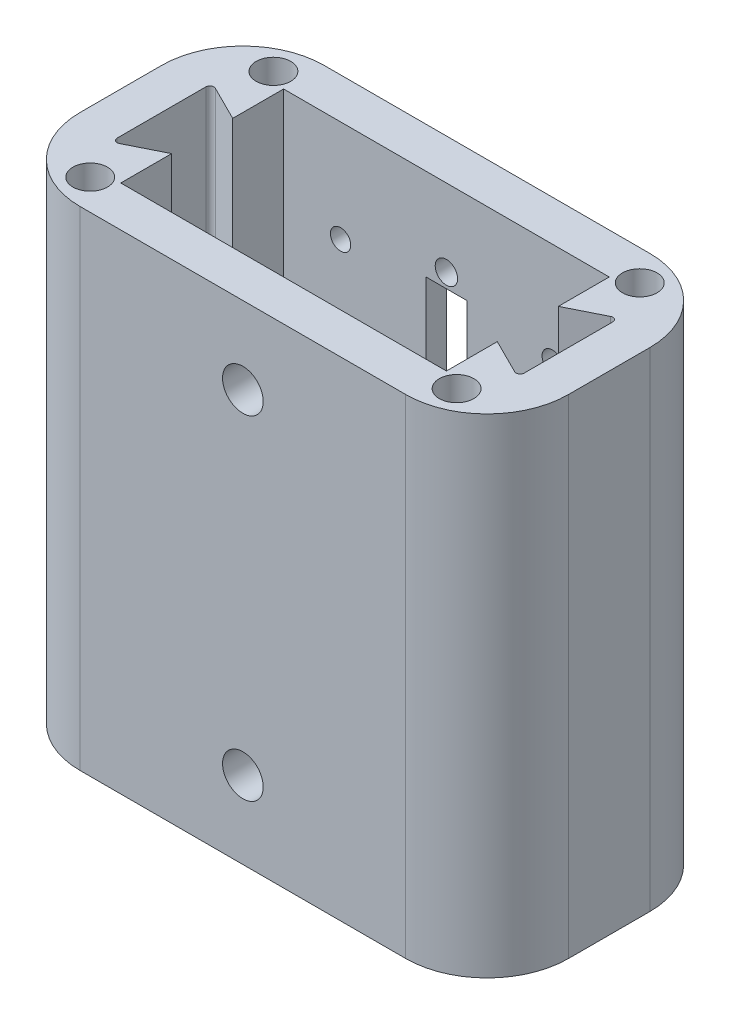
SolidWorks part; units mm, degrees
ref_plane "Front Plane" through (0, 0, 0) normal (0, 0, 1) x (1, 0, 0)
ref_plane "Top Plane" through (0, 0, 0) normal (0, 1, 0) x (1, 0, 0)
ref_plane "Right Plane" through (0, 0, 0) normal (1, 0, 0) x (0, 0, -1)
sketch "Sketch1" plane through (0, 0, 0) normal (0, 1, 0) x (1, 0, 0)
  line L1 (-30, -15) -> (30, -15)
  line L2 (-30, -15) -> (-30, 15)
  line L3 (-30, 15) -> (30, 15)
  line L4 (30, -15) -> (30, 15)
  line L5 (-30, -15) -> (30, 15) construction
  line L6 (-30, 15) -> (30, -15) construction
  line L7 (-20, -10) -> (20, -10)
  line L8 (-20, -10) -> (-20, 10)
  line L9 (-20, 10) -> (20, 10)
  line L10 (20, -10) -> (20, 10)
  line L11 (-20, -10) -> (20, 10) construction
  line L12 (-20, 10) -> (20, -10) construction
  point P0 (0, 0)
  point P7 (0, 0)
  dimension "D1" = 60
  dimension "D2" = 30
  dimension "D3" = 20
  dimension "D4" = 40
extrude "Boss-Extrude1" add sketch "Sketch1" along normal blind 5
sketch "Sketch2" plane through (0, 5, 0) normal (0, 1, 0) x (1, 0, 0)
  line L0 (20, 3.75) -> (24.2764, 5.8882)
  line L1 (25, 5.441) -> (25, -5.441)
  line L2 (24.2764, -5.8882) -> (20, -3.75)
  line L3 (20, 3.75) -> (20, -3.75) construction
  line L4 (20, -10) -> (20, 10) construction
  line L5 (0, -55) -> (0, 55) construction
  line L6 (-20, 3.75) -> (-20, -3.75) construction
  line L7 (-24.2764, -5.8882) -> (-20, -3.75)
  line L8 (-25, 5.441) -> (-25, -5.441)
  line L9 (-20, 3.75) -> (-24.2764, 5.8882)
  line L14 (30, -15) -> (30, 15)
  line L15 (30, 15) -> (-30, 15)
  line L16 (-30, 15) -> (-30, -15)
  line L17 (-30, -15) -> (30, -15)
  line L18 (30, -15) -> (30, 15)
  line L19 (30, 15) -> (-30, 15)
  line L20 (-30, 15) -> (-30, -15)
  line L21 (-30, -15) -> (30, -15)
  arc A1 (25, -5.441) -> (24.2764, -5.8882) centre (24.5, -5.441) cw
  arc A2 (24.2764, 5.8882) -> (25, 5.441) centre (24.5, 5.441) cw
  arc A3 (-24.2764, 5.8882) -> (-25, 5.441) centre (-24.5, 5.441) ccw
  arc A4 (-25, -5.441) -> (-24.2764, -5.8882) centre (-24.5, -5.441) ccw
  point P6 (25, 0)
  point P8 (20, 0)
  point P12 (25, -6.25)
  point P15 (25, 6.25)
  point P27 (-25, 6.25)
  point P28 (-25, -6.25)
  point P42 (0, 0)
  dimension "D1" = 0
  dimension "D2" = 5
  dimension "D5" = 0.5
  dimension "D3" = 7.5
  dimension "D4" = 12.5
extrude "Boss-Extrude2" add sketch "Sketch2" along normal blind 55
sketch "Sketch4" plane through (-36.2132, 0, -15) normal (0, 0, 1) x (1, 0, 0)
  line L1 (33.7132, 11.25) -> (38.7132, 11.25)
  line L2 (33.7132, 11.25) -> (33.7132, 48.75)
  line L3 (33.7132, 48.75) -> (38.7132, 48.75)
  line L4 (38.7132, 11.25) -> (38.7132, 48.75)
  line L5 (33.7132, 11.25) -> (38.7132, 48.75) construction
  line L6 (33.7132, 48.75) -> (38.7132, 11.25) construction
  line L7 (36.2132, 50.5) -> (36.2132, 9.5)
  line L8 (66.2132, 0) -> (6.2132, 0) construction
  circle A0 centre (36.2132, 50.5) radius 1.375
  circle A1 centre (36.2132, 9.5) radius 1.375
  point P0 (36.2132, 30)
  point P10 (36.2132, 30)
  dimension "D5" = 2.75
  dimension "D1" = 5
  dimension "D2" = 37.5
  dimension "D3" = 11.25
  dimension "D4" = 41
extrude "Cut-Extrude1" cut sketch "Sketch4" along normal up to surface (5 mm away) up to face at (0, 30, -10)
sketch "Sketch5" plane through (0, 0, -15) normal (0, 0, -1) x (-1, 0, 0)
  line L0 (-2.5, 48.75) -> (2.5, 11.25) construction
  line L1 (2.5, 48.75) -> (-2.5, 11.25) construction
  line L3 (-7.5, 6.25) -> (7.5, 6.25)
  line L4 (-7.5, 6.25) -> (-7.5, 53.75)
  line L5 (-7.5, 53.75) -> (7.5, 53.75)
  line L6 (7.5, 6.25) -> (7.5, 53.75)
  line L7 (-7.5, 6.25) -> (7.5, 53.75) construction
  line L8 (-7.5, 53.75) -> (7.5, 6.25) construction
  point P8 (0, 30)
  dimension "D1" = 15
  dimension "D2" = 47.5
extrude "Cut-Extrude2" cut sketch "Sketch5" against normal blind 2.5
fillet "Fillet1" radius 10 4 edges at (30, 30, -15) (-30, 30, -15) (30, 30, 15) (-30, 30, 15)
sketch "Sketch6" plane through (0, 60, 0) normal (0, 1, 0) x (1, 0, 0)
  line L1 (-22.5, -11.25) -> (22.5, -11.25) construction
  line L2 (-22.5, -11.25) -> (-22.5, 11.25) construction
  line L3 (-22.5, 11.25) -> (22.5, 11.25) construction
  line L4 (22.5, -11.25) -> (22.5, 11.25) construction
  line L5 (-22.5, -11.25) -> (22.5, 11.25) construction
  line L6 (-22.5, 11.25) -> (22.5, -11.25) construction
  circle A0 centre (-22.5, 11.25) radius 2.125
  circle A1 centre (22.5, 11.25) radius 2.125
  circle A2 centre (-22.5, -11.25) radius 2.125
  circle A3 centre (22.5, -11.25) radius 2.125
  point P0 (0, 0)
  dimension "D3" = 4.25
  dimension "D1" = 45
  dimension "D2" = 22.5
extrude "Cut-Extrude3" cut sketch "Sketch6" against normal blind 5
sketch "Sketch7" plane through (0, 0, 15) normal (0, 0, 1) x (1, 0, 0)
  circle A0 centre (0, 9.5) radius 1.375 construction
  circle A1 centre (0, 50.5) radius 1.375 construction
  circle A2 centre (0, 9.5) radius 1.375 construction
  circle A3 centre (0, 50.5) radius 1.375 construction
  circle A4 centre (0, 50.5) radius 2.5
  circle A5 centre (0, 9.5) radius 2.5
  dimension "D1" = 5
extrude "Cut-Extrude4" cut sketch "Sketch7" against normal up to surface (5 mm away) up to face at (0, 30, 10)
sketch "Sketch8" plane through (0, 0, -15) normal (0, 0, -1) x (-1, 0, 0)
  circle A0 centre (13, 47.5) radius 1.3 construction
  circle A1 centre (-13, 47.5) radius 1.3 construction
  circle A2 centre (-13, 12.5) radius 1.3 construction
  circle A3 centre (13, 12.5) radius 1.3 construction
  circle A4 centre (13, 47.5) radius 1.3 construction
  circle A5 centre (-13, 47.5) radius 1.3 construction
  circle A6 centre (-13, 12.5) radius 1.3 construction
  circle A7 centre (13, 12.5) radius 1.3 construction
  circle A8 centre (-13, 47.5) radius 1.25
  circle A9 centre (13, 47.5) radius 1.25
  circle A10 centre (-13, 12.5) radius 1.25
  circle A11 centre (13, 12.5) radius 1.25
  dimension "D1" = 2.5
extrude "Cut-Extrude5" cut sketch "Sketch8" against normal up to surface (5 mm away) up to face at (1.375, 50.5, -10)
